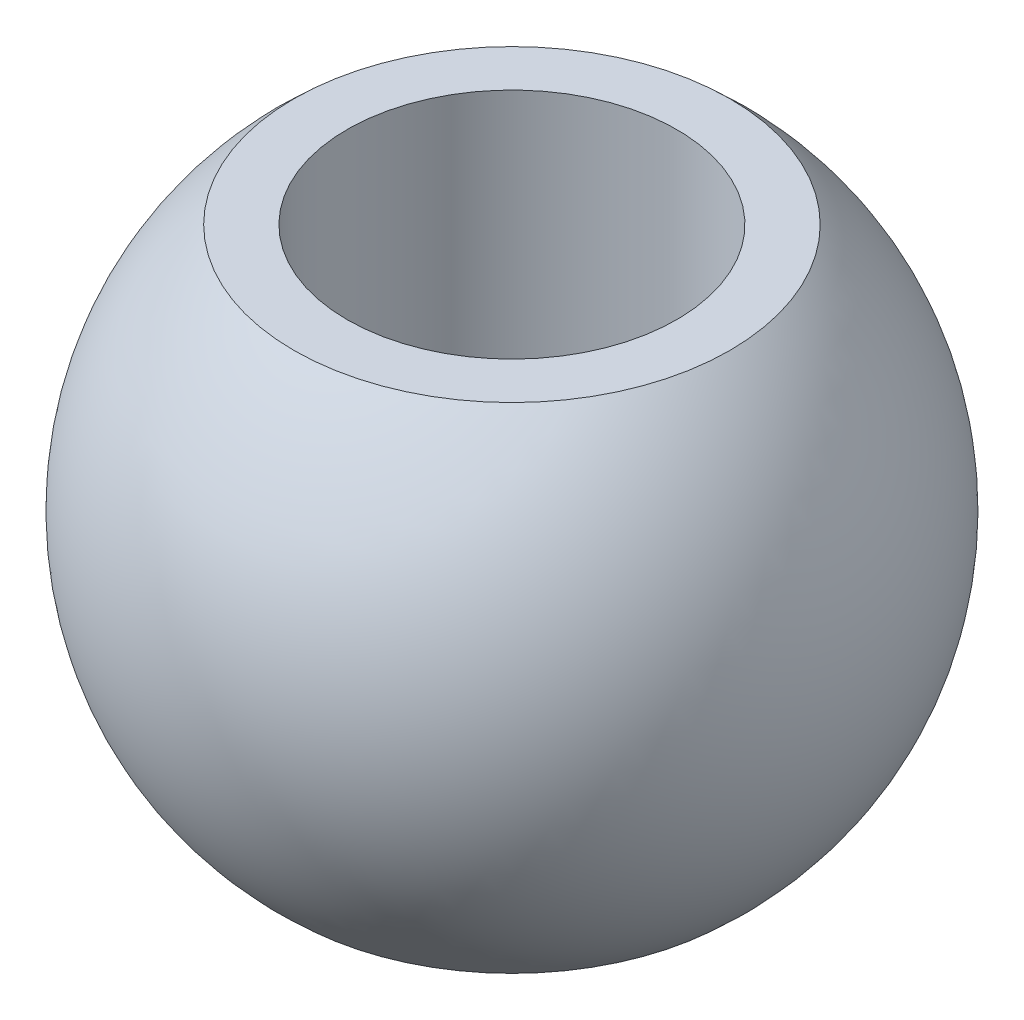
SolidWorks part; units mm, degrees
ref_plane "Front Plane" through (0, 0, 0) normal (0, 0, 1) x (1, 0, 0)
ref_plane "Top Plane" through (0, 0, 0) normal (0, 1, 0) x (1, 0, 0)
ref_plane "Right Plane" through (0, 0, 0) normal (1, 0, 0) x (0, 0, -1)
sketch "Sketch1" plane through (0, 0, 0) normal (0, 0, 1) x (1, 0, 0)
  line L0 (0, 6.35) -> (0, -6.35) construction
  line L1 (0, 6.35) -> (0, -6.35)
  arc A0 (0, -6.35) -> (0, 6.35) centre (0, 0) ccw
  dimension "D1" = 12.7
revolve "Revolve3" add sketch "Sketch1" angle 360 about L0
sketch "Sketch2" plane through (0, 0, 0) normal (0, 0, 1) x (1, 0, 0)
  line L0 (0, 4.7625) -> (0, -4.7625) construction
  line L1 (0, 6.35) -> (6.35, 6.35)
  line L2 (6.35, 6.35) -> (6.35, 4.7625)
  line L3 (6.35, 4.7625) -> (3.175, 4.7625)
  line L4 (3.175, 4.7625) -> (3.175, -4.7625)
  line L5 (3.175, -4.7625) -> (6.35, -4.7625)
  line L6 (6.35, -4.7625) -> (6.35, -6.35)
  line L7 (6.35, -6.35) -> (0, -6.35)
  line L8 (0, 6.35) -> (0, -6.35)
  dimension "D1" = 9.525
  dimension "D2" = 6.35
  dimension "D3" = 12.7
  dimension "D4" = 12.7
revolve "Cut-Revolve1" cut sketch "Sketch2" angle 360 about L0
